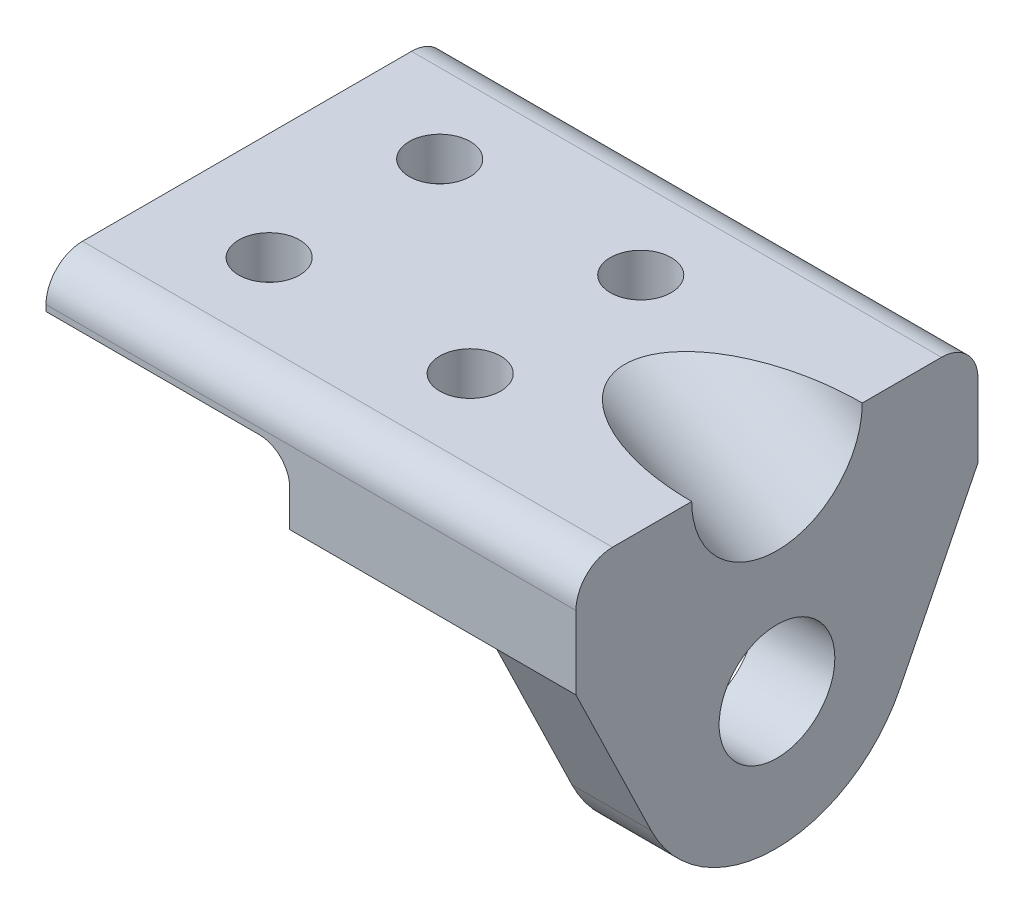
SolidWorks part; units mm, degrees
ref_plane "Front Plane" through (0, 0, 0) normal (0, 0, 1) x (1, 0, 0)
ref_plane "Top Plane" through (0, 0, 0) normal (0, 1, 0) x (1, 0, 0)
ref_plane "Right Plane" through (0, 0, 0) normal (1, 0, 0) x (0, 0, -1)
sketch "Sketch1" plane through (0, 0, 0) normal (0, 0, 1) x (1, 0, 0)
  line L0 (40, -5) -> (40, -11)
  line L1 (0, 0) -> (87, 0)
  line L2 (0, 0) -> (0, 7)
  line L3 (0, 7) -> (87, 7)
  line L4 (87, 0) -> (87, 7)
  line L5 (40, -11) -> (87, -11)
  line L6 (87, 0) -> (87, -11)
  arc A0 (40, -5) -> (35, 0) centre (35, -5) ccw
  dimension "D1" = 5
  dimension "D2" = 7
  dimension "D3" = 40
  dimension "D4" = 47
  dimension "D5" = 11
extrude "Boss-Extrude1" add sketch "Sketch1" along normal blind 66 contours L1 L4 L3 L2 | A0 L0 L5 L6 L1
fillet "Fillet1" radius 6 2 edges at (43.5, 7, 0) (43.5, 7, 66)
sketch "Sketch2" plane through (0, 7, 0) normal (0, 1, 0) x (1, 0, 0)
  line L0 (87, -66) -> (0, -66) construction
  line L1 (17.6359, -47) -> (50.6359, -47) construction
  line L2 (0, -33) -> (87, -33) construction
  line L3 (0, -60) -> (0, -6) construction
  line L4 (87, -60) -> (87, -6) construction
  circle A0 centre (50.6359, -47) radius 5
  circle A1 centre (17.6359, -47) radius 5
  circle A2 centre (50.6359, -19) radius 5
  circle A3 centre (17.6359, -19) radius 5
  dimension "D1" = 19
  dimension "D2" = 10
  dimension "D3" = 10
  dimension "D4" = 33
extrude "Cut-Extrude1" cut sketch "Sketch2" against normal through all
sketch "Sketch3" plane through (87, 0, 0) normal (1, 0, 0) x (0, 0, -1)
  line L0 (-60, 7) -> (-6, 7) construction
  line L1 (-33, 7) -> (-33, -36.5) construction
  line L2 (-66, -11) -> (-53.6563, -36.4594)
  line L3 (0, -11) -> (-12.8349, -36.6991)
  circle A0 centre (-33, -27) radius 9.5
  arc A1 (-53.6563, -36.4594) -> (-12.8349, -36.6991) centre (-33.1866, -26.5349) ccw
  dimension "D1" = 19
  dimension "D2" = 34
extrude "Boss-Extrude2" add sketch "Sketch3" against normal blind 13
ref_plane "Plane1" through (0, 0, 33) normal (0, 0, 1) x (1, 0, 0)
sketch "Sketch8" plane through (0, 0, 33) normal (0, 0, 1) x (1, 0, 0)
  line L1 (0, 7) -> (87, 7) construction
  line L7 (87, -11) -> (87, 1) construction
  line L8 (87, -7) -> (62, 7)
sketch "Sketch9" plane through (87, 0, 0) normal (1, 0, 0) x (0, 0, -1)
  line L0 (-60, 7) -> (-6, 7) construction
  circle A0 centre (-33, 7) radius 14
  dimension "D1" = 28
sweep "Cut-Sweep4" cut profiles "Sketch9" path "Sketch8"
